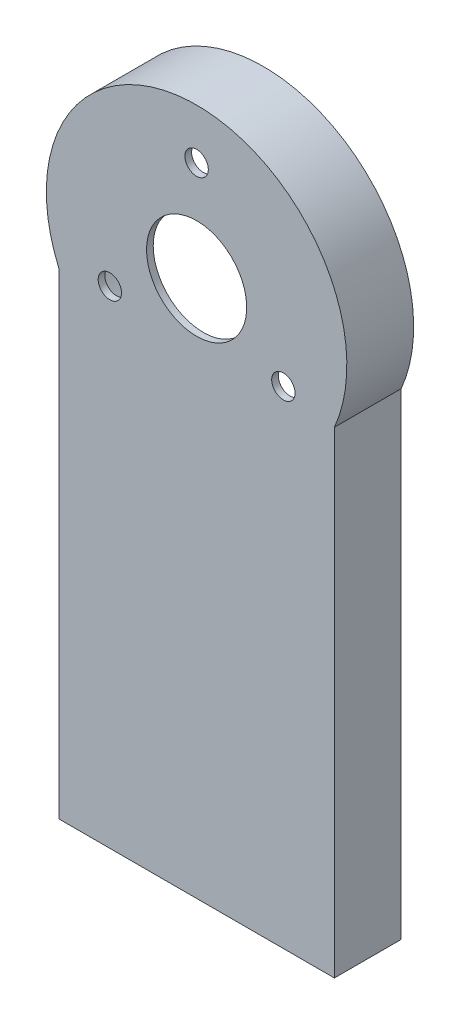
SolidWorks part; units mm, degrees
ref_plane "Front Plane" through (0, 0, 0) normal (0, 0, 1) x (1, 0, 0)
ref_plane "Top Plane" through (0, 0, 0) normal (0, 1, 0) x (1, 0, 0)
ref_plane "Right Plane" through (0, 0, 0) normal (1, 0, 0) x (0, 0, -1)
sketch "Sketch1" plane through (0, 0, 0) normal (0, 0, 1) x (1, 0, 0)
  line L1 (-20.6318, -8.9767) -> (-20.6318, -80.4)
  line L2 (20.6318, -8.9767) -> (20.6318, -80.4)
  line L3 (-20.6318, -80.4) -> (20.6318, -80.4)
  line L4 (0, 0) -> (0, 22.5) construction
  arc A0 (20.6318, -8.9767) -> (-20.6318, -8.9767) centre (0, 0) ccw
  point P3 (0, -80.4)
  dimension "D1" = 45
  dimension "D2" = 102.9
extrude "Boss-Extrude1" add sketch "Sketch1" along normal blind 10
sketch "Sketch2" plane through (0, 0, 0) normal (0, 0, -1) x (-1, 0, 0)
  line L0 (0, 0) -> (0, 22.5) construction
  circle A0 centre (0, 15) radius 1.75
  arc A1 (20.6318, -8.9767) -> (-20.6318, -8.9767) centre (0, 0) ccw construction
  circle A2 centre (12.9904, -7.5) radius 1.75
  circle A3 centre (-12.9904, -7.5) radius 1.75
  point P14 (0, 0)
  dimension "D1" = 3.5
  dimension "D2" = 15
  dimension "D3" = 3
extrude "Cut-Extrude1" cut sketch "Sketch2" against normal blind 10
sketch "Sketch3" plane through (0, 0, 0) normal (0, 0, -1) x (-1, 0, 0)
  circle A0 centre (0, 0) radius 21.1
  dimension "D1" = 42.2
extrude "Cut-Extrude2" cut sketch "Sketch3" against normal blind 9
sketch "Sketch4" plane through (0, 0, 0) normal (0, 0, -1) x (-1, 0, 0)
  circle A0 centre (0, 0) radius 7.5
  dimension "D1" = 15
extrude "Cut-Extrude3" cut sketch "Sketch4" against normal blind 10
